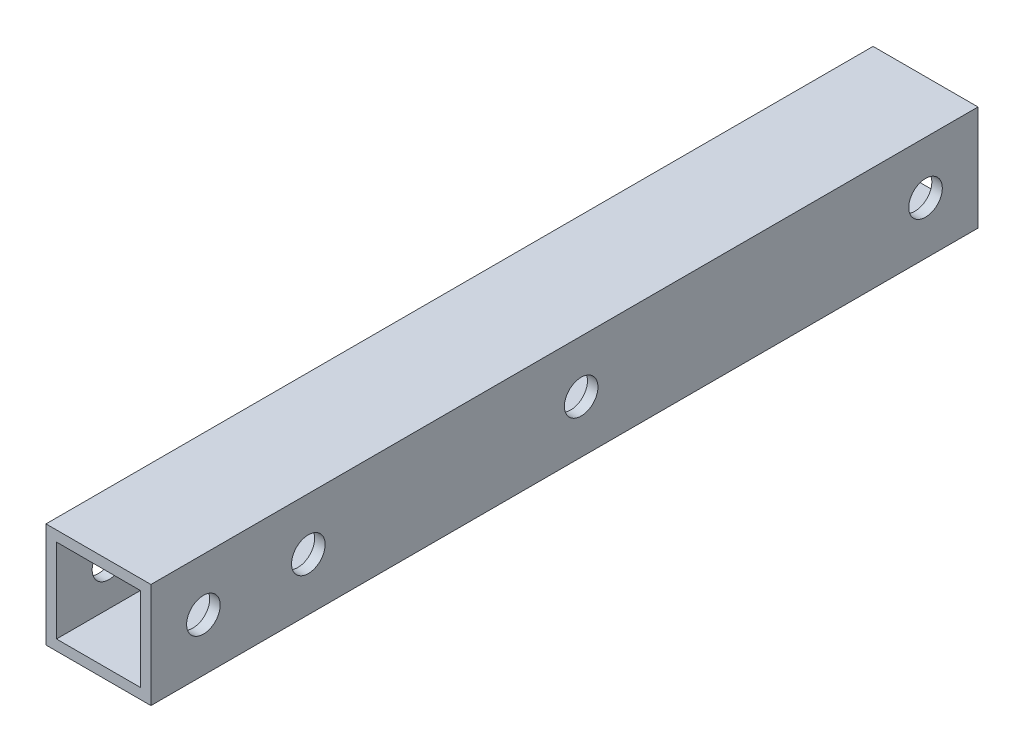
SolidWorks part; units mm, degrees
ref_plane "正面" through (0, 0, 0) normal (0, 0, 1) x (1, 0, 0)
ref_plane "平面" through (0, 0, 0) normal (0, 1, 0) x (1, 0, 0)
ref_plane "右側面" through (0, 0, 0) normal (1, 0, 0) x (0, 0, -1)
sketch "ｽｹｯﾁ1" plane through (0, 0, 0) normal (0, 0, 1) x (1, 0, 0)
  line L1 (-5, -5) -> (5, -5)
  line L2 (-5, -5) -> (-5, 5)
  line L3 (-5, 5) -> (5, 5)
  line L4 (5, -5) -> (5, 5)
  line L5 (-5, -5) -> (5, 5) construction
  line L6 (-5, 5) -> (5, -5) construction
  line L7 (-4, -4) -> (4, -4)
  line L8 (-4, -4) -> (-4, 4)
  line L9 (-4, 4) -> (4, 4)
  line L10 (4, -4) -> (4, 4)
  line L11 (-4, -4) -> (4, 4) construction
  line L12 (-4, 4) -> (4, -4) construction
  point P0 (0, 0)
  point P6 (0, 0)
  dimension "D1" = 1
  dimension "D2" = 10
  dimension "D3" = 10
extrude "ﾎﾞｽ - 押し出し1" add sketch "ｽｹｯﾁ1" along normal blind 78.8186
sketch "ｽｹｯﾁ2" plane through (5, 0, 0) normal (1, 0, 0) x (0, 0, -1)
  line L0 (-78.8186, -5) -> (0, -5) construction
  line L1 (0, -5) -> (0, 5) construction
  line L2 (-78.8186, -5) -> (-78.8186, 5) construction
  circle A0 centre (-5, 0) radius 1.6
  circle A1 centre (-73.8186, 0) radius 1.6
  dimension "D1" = 3.2
  dimension "D2" = 5
  dimension "D3" = 5
  dimension "D4" = 3.2
  dimension "D5" = 5
  dimension "D6" = 5
extrude "ｶｯﾄ - 押し出し1" cut sketch "ｽｹｯﾁ2" against normal through all
sketch "ｽｹｯﾁ3" plane through (-5, 0, 0) normal (-1, 0, 0) x (0, 0, 1)
  line L0 (78.8186, 5) -> (78.8186, -5) construction
  line L1 (78.8186, -5) -> (0, -5) construction
  circle A0 centre (63.8186, 0) radius 1.6
  circle A1 centre (37.8186, 0) radius 1.6
  dimension "D1" = 3.2
  dimension "D2" = 3.2
  dimension "D3" = 26
  dimension "D4" = 15
  dimension "D5" = 5
  dimension "D6" = 5
extrude "ｶｯﾄ - 押し出し3" cut sketch "ｽｹｯﾁ3" against normal through all
